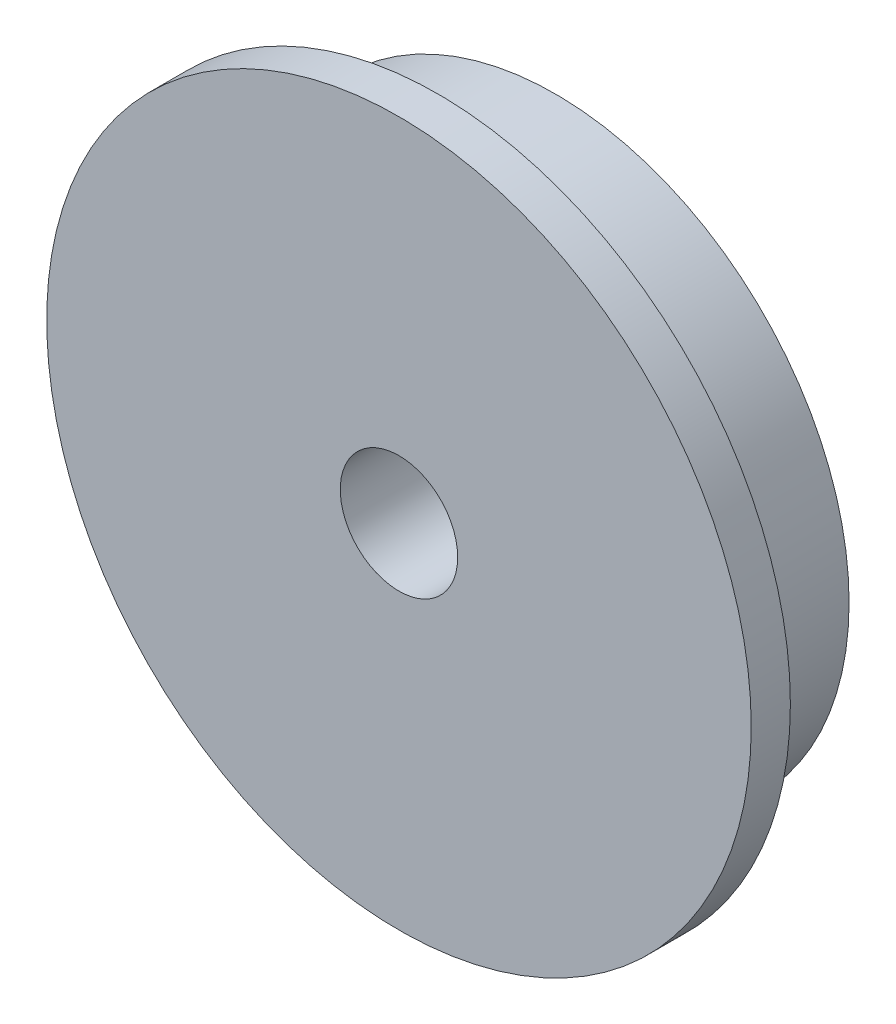
SolidWorks part; units mm, degrees
ref_plane "前视基准面" through (0, 0, 0) normal (0, 0, 1) x (1, 0, 0)
ref_plane "上视基准面" through (0, 0, 0) normal (0, 1, 0) x (1, 0, 0)
ref_plane "右视基准面" through (0, 0, 0) normal (1, 0, 0) x (0, 0, -1)
other "Configuration Table"
sketch "草图1" plane through (0, 0, 0) normal (0, 0, 1) x (1, 0, 0)
  circle A0 centre (0, 0) radius 15
  circle A1 centre (0, 0) radius 3
  dimension "D1" = 30
  dimension "D2" = 6
extrude "凸台-拉伸1" add sketch "草图1" along normal blind 8
sketch "草图2" plane through (0, 0, 8) normal (0, 0, 1) x (1, 0, 0)
  circle A0 centre (0, 0) radius 3
  circle A1 centre (0, 0) radius 18
  dimension "D1" = 36
extrude "凸台-拉伸2" add sketch "草图2" against normal blind 2
